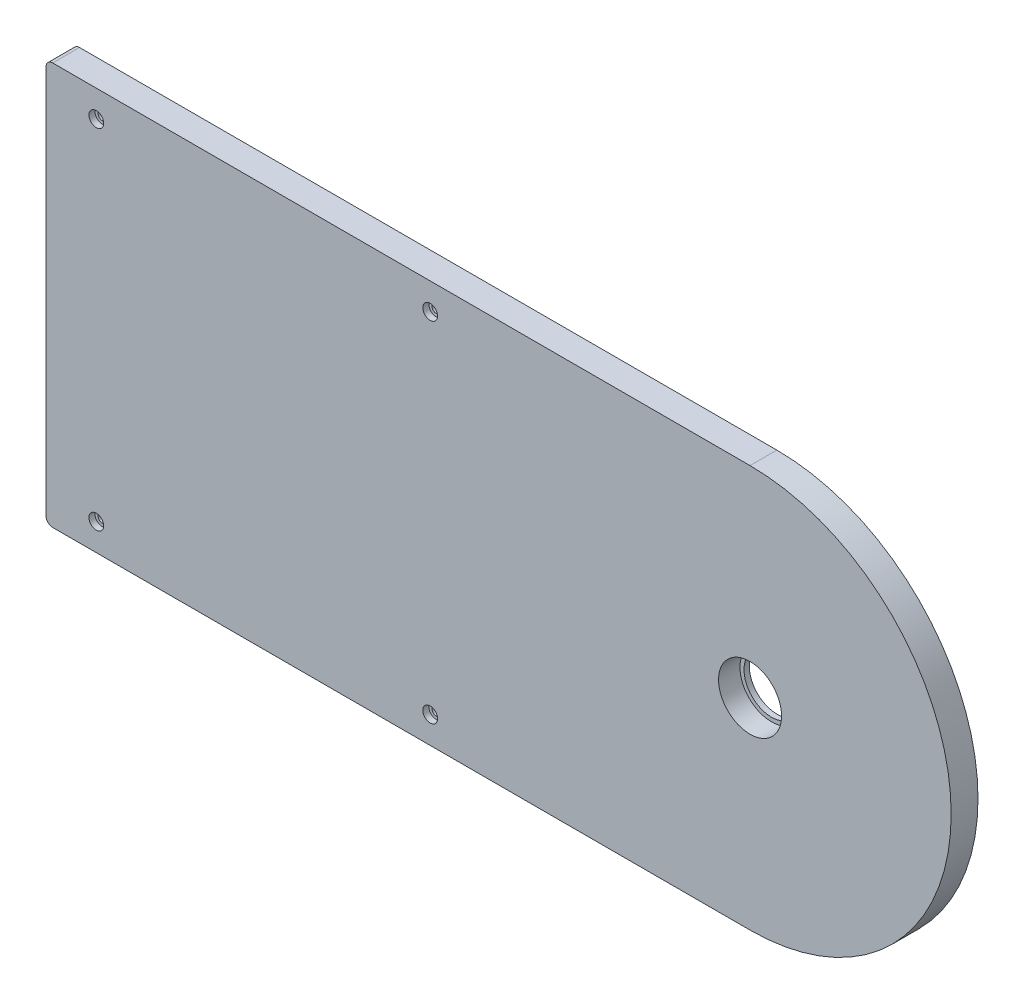
SolidWorks part; units mm, degrees
material "5052-H32"
ref_plane "Front Plane" through (0, 0, 0) normal (0, 0, 1) x (1, 0, 0)
ref_plane "Top Plane" through (0, 0, 0) normal (0, 1, 0) x (1, 0, 0)
ref_plane "Right Plane" through (0, 0, 0) normal (1, 0, 0) x (0, 0, -1)
sketch "Sketch1" plane through (0, 0, 0) normal (0, 0, 1) x (1, 0, 0)
  line L0 (0, 150) -> (-525, 150)
  line L1 (-525, 150) -> (-525, -150)
  line L2 (-525, -150) -> (0, -150)
  arc A1 (0, -150) -> (0, 150) centre (0, 0) ccw
  circle A2 centre (0, 0) radius 20.5
  dimension "D2" = 41
  dimension "D1" = 300
  dimension "D3" = 525
  dimension "D4" = 0
extrude "Boss-Extrude1" add sketch "Sketch1" along normal blind 20
sketch "Sketch2" plane through (0, 0, 20) normal (0, 0, 1) x (1, 0, 0)
  circle A0 centre (0, 0) radius 23.5
  dimension "D1" = 47
extrude "Cut-Extrude1" cut sketch "Sketch2" against normal blind 16
sketch "Sketch4" plane through (0, 0, 0) normal (0, 0, -1) x (-1, 0, 0)
  line L0 (525, 150) -> (525, -150) construction
  line L1 (525, -134) -> (206.25, -134)
  line L2 (525, -134) -> (525, -126)
  line L3 (525, -126) -> (206.25, -126)
  line L4 (206.25, -134) -> (206.25, -126)
  line L6 (525, 126) -> (206.25, 126)
  line L7 (525, 126) -> (525, 134)
  line L8 (525, 134) -> (206.25, 134)
  line L9 (206.25, 126) -> (206.25, 134)
  point P10 (525, 130)
  point P11 (525, -130)
  point P12 (206.25, 130)
  dimension "D1" = 8
  dimension "D2" = 8
  dimension "D3" = 260
  dimension "D4" = 130
  dimension "D5" = 318.75
extrude "Boss-Extrude2" add sketch "Sketch4" along normal blind 3
sketch "Sketch3" plane through (0, 0, 20) normal (0, 0, 1) x (1, 0, 0)
  line L0 (-525, 150) -> (-525, -150) construction
  circle A0 centre (-238.5, 130) radius 3.25
  circle A1 centre (-487.5, 130) radius 3.25
  circle A2 centre (-487.5, -130) radius 3.25
  circle A3 centre (-238.5, -130) radius 3.25
  dimension "D5" = 6.5
  dimension "D1" = 260
  dimension "D2" = 130
  dimension "D3" = 37.5
  dimension "D4" = 249
extrude "Cut-Extrude2" cut sketch "Sketch3" against normal through all
sketch "Sketch5" plane through (0, 0, 20) normal (0, 0, 1) x (1, 0, 0)
  circle A0 centre (-487.5, 130) radius 5.5
  circle A1 centre (-238.5, 130) radius 5.5
  circle A2 centre (-238.5, -130) radius 5.5
  circle A3 centre (-487.5, -130) radius 5.5
  dimension "D1" = 11
extrude "Cut-Extrude3" cut sketch "Sketch5" against normal blind 4.5
fillet "Fillet1" radius 5 2 edges at (-525, 150, 10) (-525, -150, 10)
